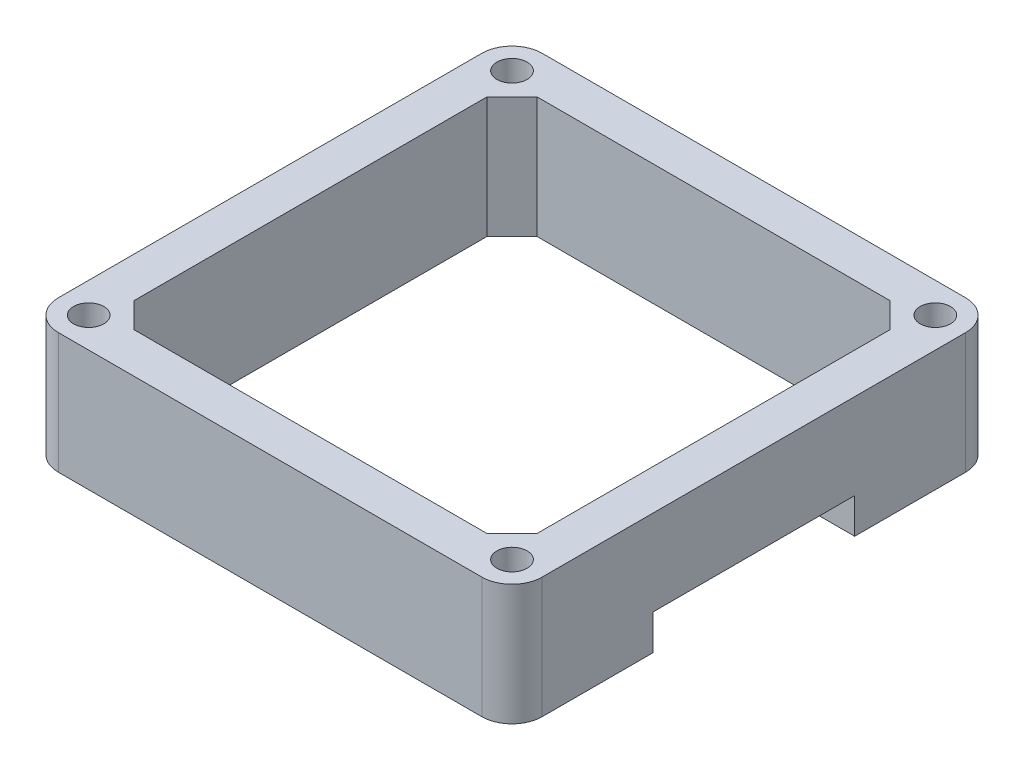
SolidWorks part; units mm, degrees
ref_plane "Front Plane" through (0, 0, 0) normal (0, 0, 1) x (1, 0, 0)
ref_plane "Top Plane" through (0, 0, 0) normal (0, 1, 0) x (1, 0, 0)
ref_plane "Right Plane" through (0, 0, 0) normal (1, 0, 0) x (0, 0, -1)
sketch "Sketch3" plane through (0, 0, 0) normal (0, 1, 0) x (1, 0, 0)
  line L0 (-14.4411, 24) -> (61.8307, 24) construction
  line L1 (3, 0) -> (45, 0)
  line L2 (0, 3) -> (0, 45)
  line L3 (3, 48) -> (45, 48)
  line L4 (48, 3) -> (48, 45)
  line L5 (24, 63.2088) -> (24, -13.6353) construction
  line L6 (4, 61.6313) -> (4, -6.5378) construction
  line L7 (44, 55.0612) -> (44, -10.615) construction
  line L8 (4, 41.5) -> (6.5, 44)
  line L9 (6.5, 44) -> (41.5, 44)
  line L10 (4, 41.5) -> (4, 6.5)
  line L11 (6.5, 4) -> (41.5, 4)
  line L12 (44, 41.5) -> (44, 6.5)
  line L13 (41.5, 44) -> (44, 41.5)
  line L14 (41.5, 4) -> (44, 6.5)
  line L15 (4, 6.5) -> (6.5, 4)
  circle A0 centre (3, 45) radius 1.5
  circle A1 centre (3, 3) radius 1.5
  circle A2 centre (45, 3) radius 1.5
  circle A3 centre (45, 45) radius 1.5
  arc A4 (3, 0) -> (0, 3) centre (3, 3) cw
  arc A5 (45, 0) -> (48, 3) centre (45, 3) ccw
  arc A6 (45, 48) -> (48, 45) centre (45, 45) cw
  arc A7 (0, 45) -> (3, 48) centre (3, 45) cw
  point P20 (0, 0)
  point P27 (0, 48)
  point P31 (4, 44)
  point P32 (44, 4)
  point P33 (4, 4)
  point P34 (44, 44)
  dimension "D2" = 3
  dimension "D6" = 3
  dimension "D7" = 3
  dimension "D1" = 48
  dimension "D3" = 3
  dimension "D4" = 24
  dimension "D5" = 24
  dimension "D8" = 4
  dimension "D9" = 4
  dimension "D10" = 40
  dimension "D11" = 4
  dimension "D12" = 4
  dimension "D13" = 40
extrude "Boss-Extrude1" add sketch "Sketch3" along normal blind 12
sketch "Sketch4" plane through (48, 0, 0) normal (1, 0, 0) x (0, 0, -1)
  line L0 (3, 0) -> (45, 0) construction
  line L1 (14, 0) -> (34, 0)
  line L2 (14, 0) -> (14, 3.5)
  line L3 (14, 3.5) -> (34, 3.5)
  line L4 (34, 0) -> (34, 3.5)
  line L5 (48, 12) -> (48, 0) construction
  dimension "D1" = 3.5
  dimension "D2" = 20
  dimension "D3" = 14
extrude "Cut-Extrude1" cut sketch "Sketch4" against normal up to surface (4 mm away) up to face at (44, 6, -24)
